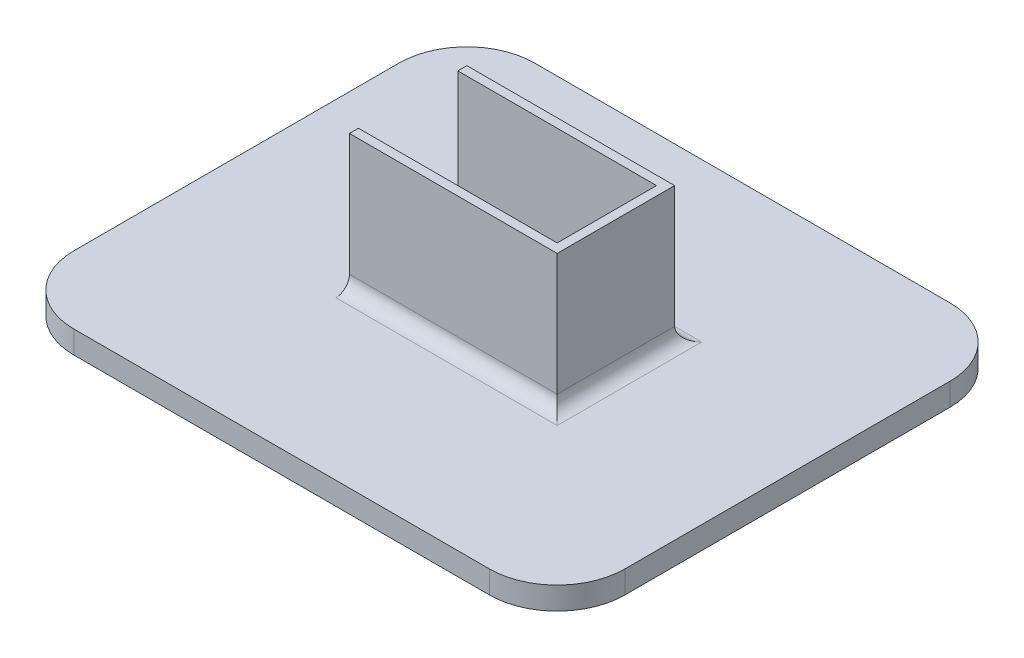
SolidWorks part; units mm, degrees
ref_plane "Front Plane" through (0, 0, 0) normal (0, 0, 1) x (1, 0, 0)
ref_plane "Top Plane" through (0, 0, 0) normal (0, 1, 0) x (1, 0, 0)
ref_plane "Right Plane" through (0, 0, 0) normal (1, 0, 0) x (0, 0, -1)
sketch "Sketch1" plane through (0, 0, 0) normal (0, 1, 0) x (1, 0, 0)
  line L4 (-21, -11) -> (21, 11) construction
  line L5 (-21, 11) -> (21, -11) construction
  line L6 (-61, 51) -> (61, 51)
  line L7 (-21, -11) -> (21, -11) construction
  line L8 (-21, -11) -> (-21, 11) construction
  line L9 (-21, 11) -> (21, 11) construction
  line L10 (21, -11) -> (21, 11) construction
  line L11 (-21, -11) -> (21, 11) construction
  line L12 (-21, 11) -> (21, -11) construction
  line L13 (61, -51) -> (61, 51)
  line L14 (-61, -51) -> (61, -51)
  line L15 (-61, -51) -> (-61, 51)
  point P0 (0, 0)
  point P1 (0, 0)
  dimension "D1" = 42
  dimension "D2" = 22
  dimension "D3" = 40
extrude "Boss-Extrude1" add sketch "Sketch1" along normal blind 5
sketch "Sketch2" plane through (0, 5, 0) normal (0, 1, 0) x (1, 0, 0)
  line L0 (-21, -11) -> (21, -11) construction
  line L1 (-21, -11) -> (-21, 11) construction
  line L2 (-21, 11) -> (21, 11) construction
  line L3 (21, -11) -> (21, 11) construction
  line L4 (-21, -11) -> (21, -11)
  line L5 (-21, -11) -> (-21, 11)
  line L6 (-21, 11) -> (21, 11)
  line L7 (21, -11) -> (21, 11)
  line L8 (23, -13) -> (23, 13)
  line L9 (-23, 13) -> (23, 13)
  line L10 (-23, -13) -> (-23, 13)
  line L11 (-23, -13) -> (23, -13)
  dimension "D1" = 2
extrude "Boss-Extrude2" add sketch "Sketch2" along normal blind 30
sketch "Sketch3" plane through (-23, 0, 0) normal (-1, 0, 0) x (0, 0, 1)
  line L4 (-11, 5) -> (11, 5)
  line L5 (-11, 35) -> (-11, 5)
  line L6 (11, 35) -> (-11, 35)
  line L7 (11, 5) -> (11, 35)
  line L8 (-11, 5) -> (11, 5)
  line L9 (-11, 35) -> (-11, 5)
  line L10 (11, 35) -> (-11, 35)
  line L11 (11, 5) -> (11, 35)
  dimension "D1" = 0
extrude "Cut-Extrude1" cut sketch "Sketch3" against normal up to surface (2 mm away) up to face at (-21, 20, 0)
fillet "Fillet1" radius 3 3 edges at (0, 5, -13) (23, 5, 0) (0, 5, 13)
fillet "Fillet2" radius 15 4 edges at (-61, 2.5, -51) (61, 2.5, -51) (61, 2.5, 51) (-61, 2.5, 51)
